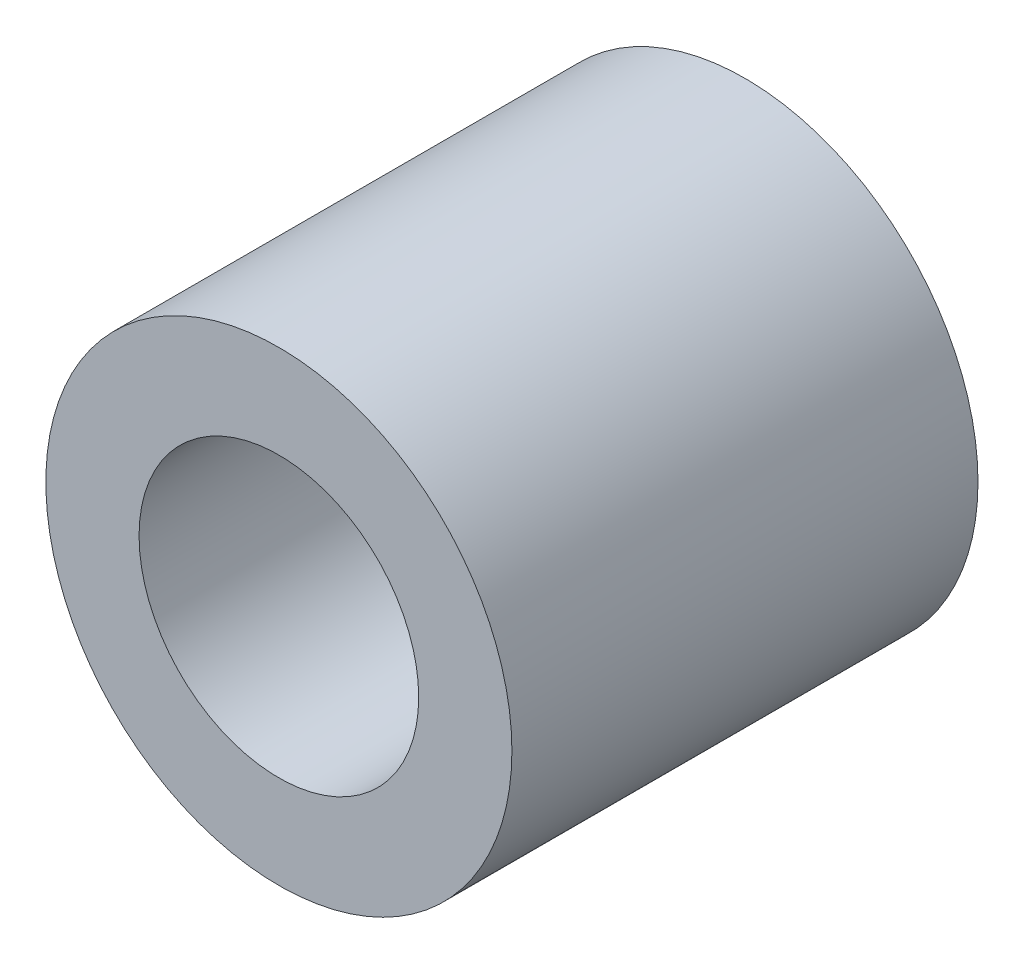
SolidWorks part; units mm, degrees
ref_plane "Front Plane" through (0, 0, 0) normal (0, 0, 1) x (1, 0, 0)
ref_plane "Top Plane" through (0, 0, 0) normal (0, 1, 0) x (1, 0, 0)
ref_plane "Right Plane" through (0, 0, 0) normal (1, 0, 0) x (0, 0, -1)
sketch "Sketch2" plane through (0, 0, 0) normal (0, 0, 1) x (1, 0, 0)
  circle A0 centre (0, 0) radius 5
extrude "Boss-Extrude1" add sketch "Sketch2" along normal blind 10
sketch "Sketch3" plane through (0, 0, 0) normal (0, 0, -1) x (-1, 0, 0)
  line L0 (1.9088, 0.5969) -> (0.8309, -1.8193)
  arc A0 (1.9088, 0.5969) -> (0.8309, -1.8193) centre (0, 0) ccw
  dimension "D1" = 1.5
extrude "Cut-Extrude1" cut sketch "Sketch3" against normal blind 5
sketch "Sketch4" plane through (0, 0, 10) normal (0, 0, 1) x (1, 0, 0)
  circle A0 centre (0, 0) radius 3
  dimension "D1" = 6
extrude "Cut-Extrude2" cut sketch "Sketch4" against normal blind 5
